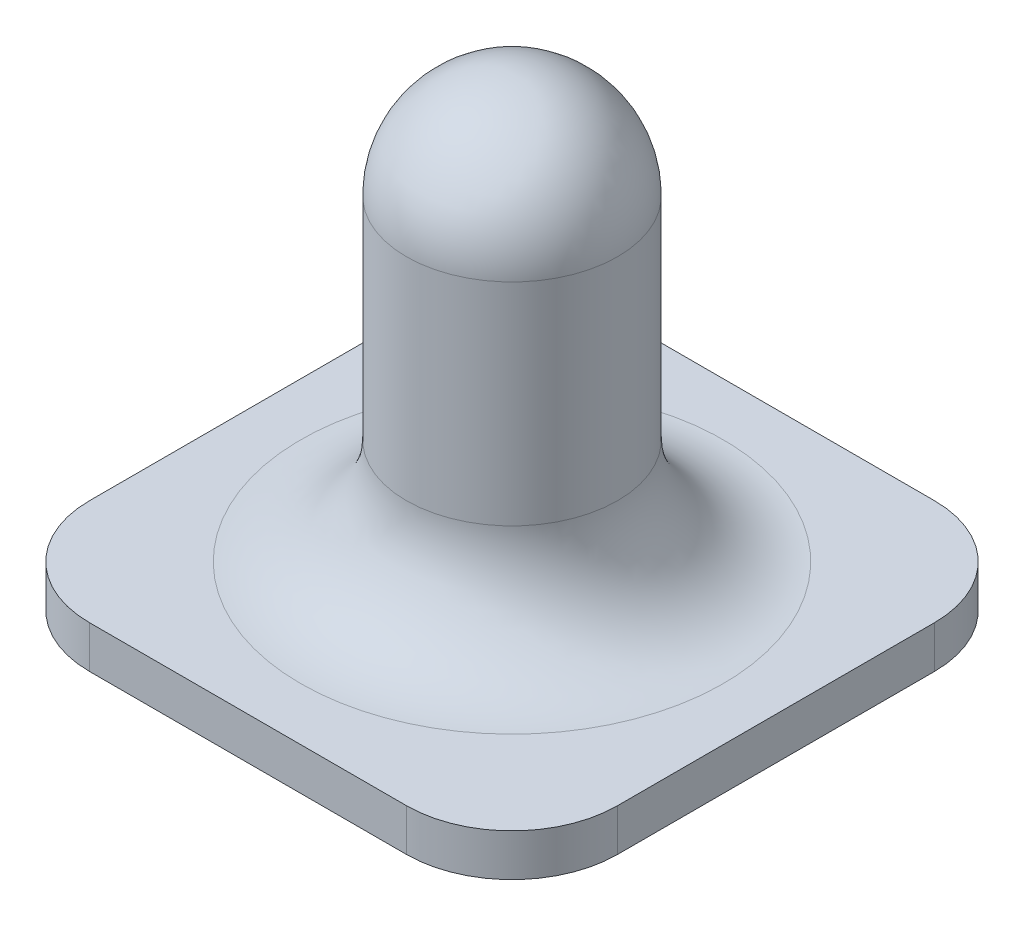
SolidWorks part; units mm, degrees
ref_plane "前视基准面" through (0, 0, 0) normal (0, 0, 1) x (1, 0, 0)
ref_plane "上视基准面" through (0, 0, 0) normal (0, 1, 0) x (1, 0, 0)
ref_plane "右视基准面" through (0, 0, 0) normal (1, 0, 0) x (0, 0, -1)
other "Configuration Table"
sketch "草图1" plane through (0, 0, 0) normal (0, 1, 0) x (1, 0, 0)
  line L1 (0, 0) -> (50, 0)
  line L2 (0, 0) -> (0, -50)
  line L3 (0, -50) -> (50, -50)
  line L4 (50, 0) -> (50, -50)
  dimension "D1" = 50
  dimension "D2" = 50
extrude "凸台-拉伸1" add sketch "草图1" along normal blind 4
sketch "草图2" plane through (0, 4, 0) normal (0, 1, 0) x (1, 0, 0)
  line L1 (0, 0) -> (0, -50) construction
  line L2 (50, 0) -> (0, 0) construction
  circle A0 centre (25, -25) radius 10
  point P4 (0, -25)
  point P7 (25, 0)
  dimension "D1" = 0
  dimension "D2" = 0
  dimension "D3" = 20
extrude "凸台-拉伸2" add sketch "草图2" along normal blind 40
fillet "圆角1" radius 10 1 edges at (25, 4, 35)
fillet "圆角2" radius 10 1 edges at (25, 44, 35)
fillet "圆角3" radius 10 4 edges at (50, 2, 0) (50, 2, 50) (0, 2, 50) (0, 2, 0)
